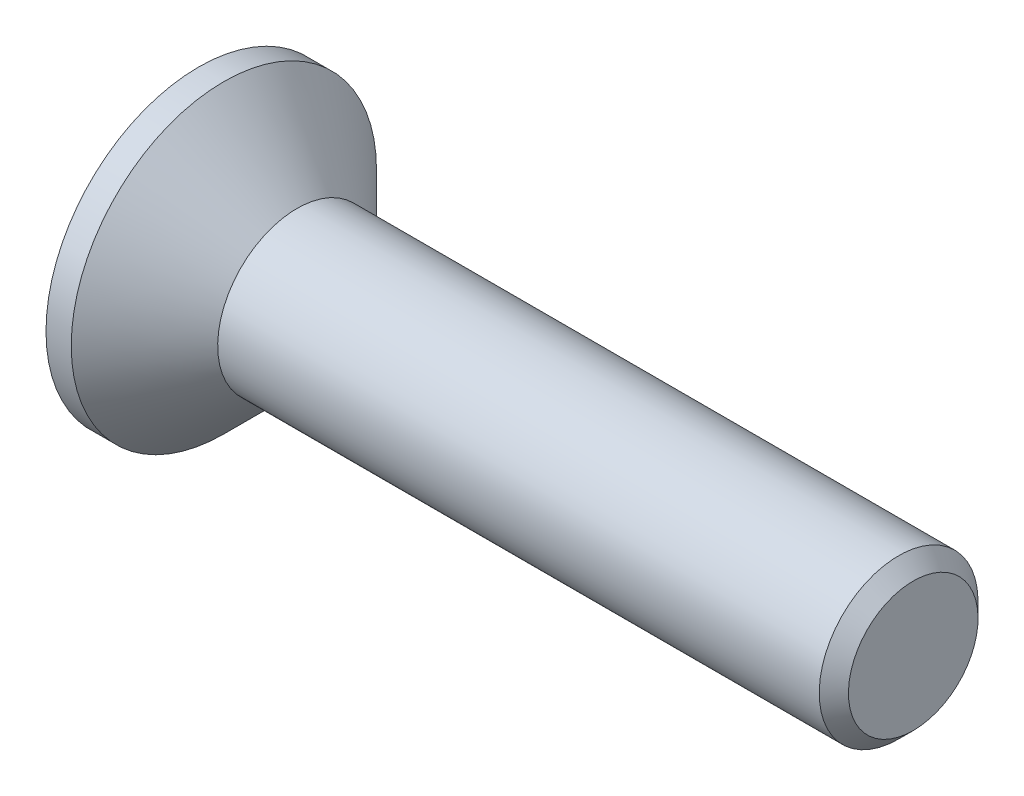
SolidWorks part; units mm, degrees
ref_plane "前基準面" through (0, 0, 0) normal (0, 0, 1) x (1, 0, 0)
ref_plane "上基準面" through (0, 0, 0) normal (0, 1, 0) x (1, 0, 0)
ref_plane "右基準面" through (0, 0, 0) normal (1, 0, 0) x (0, 0, -1)
ref_plane "平面1"
sketch "草圖1" plane through (0, 0, 0) normal (0, 0, 1) x (1, 0, 0)
  line L0 (45, 0) -> (45, 5)
  line L1 (45, 5) -> (13, 5)
  line L2 (13, 5) -> (12.0798, 5)
  line L3 (12.0798, 5) -> (6.2, 5)
  line L4 (6.2, 5) -> (1.59, 9.61)
  line L5 (1.59, 9.61) -> (0, 9.61)
  line L6 (0, 9.61) -> (0, 3.4641)
  line L7 (0, 3.4641) -> (4.18, 3.4641)
  line L8 (4.18, 3.4641) -> (6.18, 0)
  line L9 (6.18, 0) -> (45, 0)
  line L10 (6.18, 0) -> (45, 0) construction
revolve "本體" add sketch "草圖1" angle 360 about L10
cosmetic thread "裝飾螺紋線1" parameters "D1"=32, "D2"=8.344
ref_plane "平面2"
sketch "草圖2" plane through (0, 0, 0) normal (-1, 0, 0) x (0, 0, 1)
  line L0 (3.4641, 0) -> (1.7321, 3)
  line L1 (1.7321, 3) -> (-1.7321, 3)
  line L2 (-1.7321, 3) -> (-3.4641, 0)
  line L3 (-3.4641, 0) -> (-1.7321, -3)
  line L4 (-1.7321, -3) -> (1.7321, -3)
  line L5 (1.7321, -3) -> (3.4641, 0)
  arc A0 (0, 3.4641) -> (3.4641, 0) centre (0, 0) ccw
  arc A1 (3.4641, 0) -> (0, 3.4641) centre (0, 0) ccw
extrude "螺紋" add sketch "草圖2" against normal up to next contours A1 A0
chamfer "倒角1" distance 0.9202 distance2 0.9202 1 edges at (45, -5, 0)
